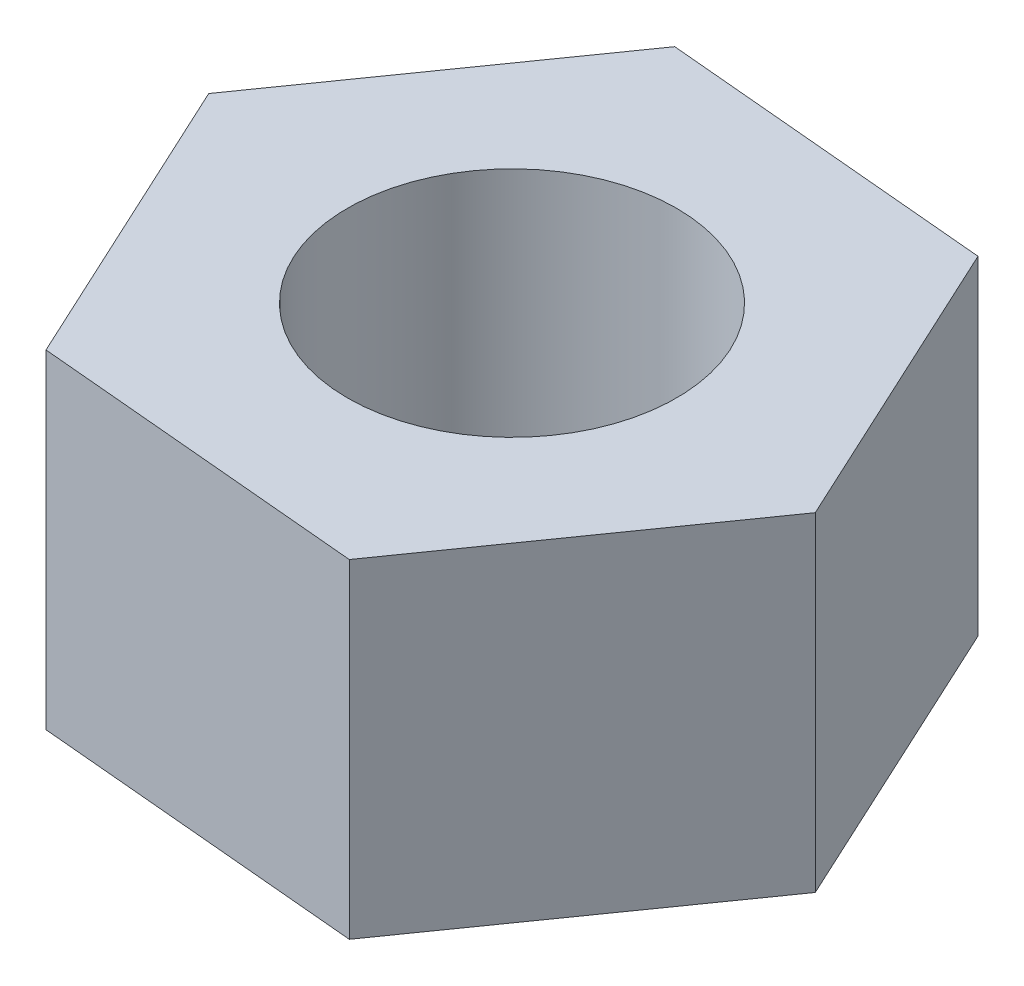
SolidWorks part; units mm, degrees
ref_plane "Front Plane" through (0, 0, 0) normal (0, 0, 1) x (1, 0, 0)
ref_plane "Top Plane" through (0, 0, 0) normal (0, 1, 0) x (1, 0, 0)
ref_plane "Right Plane" through (0, 0, 0) normal (1, 0, 0) x (0, 0, -1)
sketch "Sketch1" plane through (0, 0, 0) normal (0, 1, 0) x (1, 0, 0)
  line L7 (1.711, -3.6901) -> (4.0512, -0.3633)
  line L8 (4.0512, -0.3633) -> (2.3402, 3.3268)
  line L9 (2.3402, 3.3268) -> (-1.711, 3.6901)
  line L10 (-1.711, 3.6901) -> (-4.0512, 0.3633)
  line L11 (-4.0512, 0.3633) -> (-2.3402, -3.3268)
  line L12 (-2.3402, -3.3268) -> (1.711, -3.6901)
  circle A0 centre (0, 0) radius 2
  circle A1 centre (0, 0) radius 3.5225 construction
extrude "Boss-Extrude1" add sketch "Sketch1" along normal blind 4
